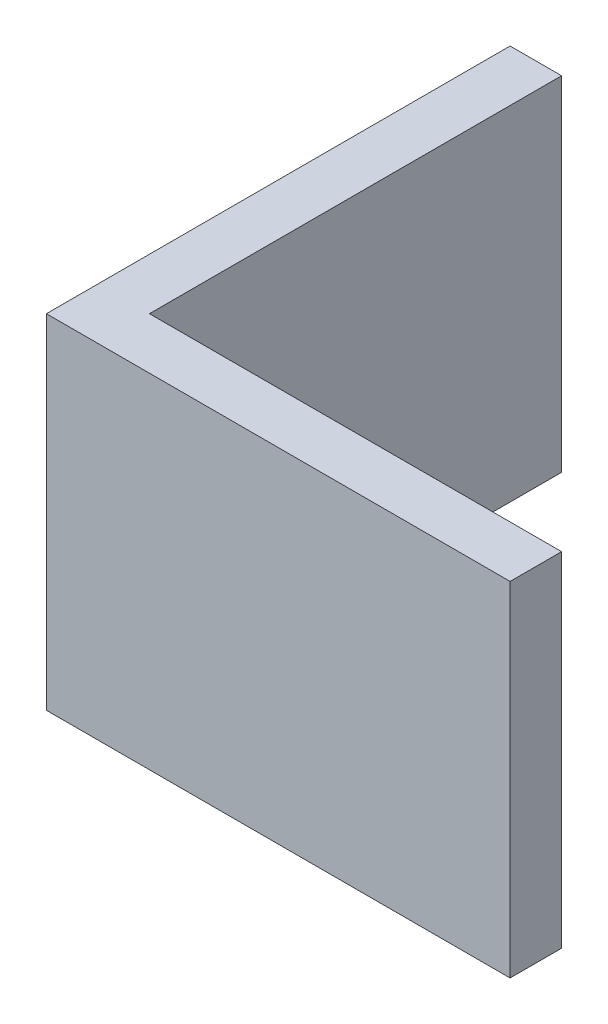
SolidWorks part; units mm, degrees
material "Pine"
ref_plane "Front" through (0, 0, 0) normal (0, 0, 1) x (1, 0, 0)
ref_plane "Top" through (0, 0, 0) normal (0, 1, 0) x (1, 0, 0)
ref_plane "Right" through (0, 0, 0) normal (1, 0, 0) x (0, 0, -1)
sketch "Sketch1" plane through (0, 0, 0) normal (0, 1, 0) x (1, 0, 0)
  line L0 (0, 0) -> (0, 171.45)
  line L1 (0, 0) -> (171.45, 0)
  line L2 (19.05, 19.05) -> (171.45, 19.05)
  line L3 (19.05, 19.05) -> (19.05, 171.45)
  line L4 (0, 171.45) -> (19.05, 171.45)
  line L5 (171.45, 19.05) -> (171.45, 0)
  dimension "D1" = 171.45
  dimension "D2" = 19.05
extrude "Boss-Extrude1" add sketch "Sketch1" along normal blind 127
